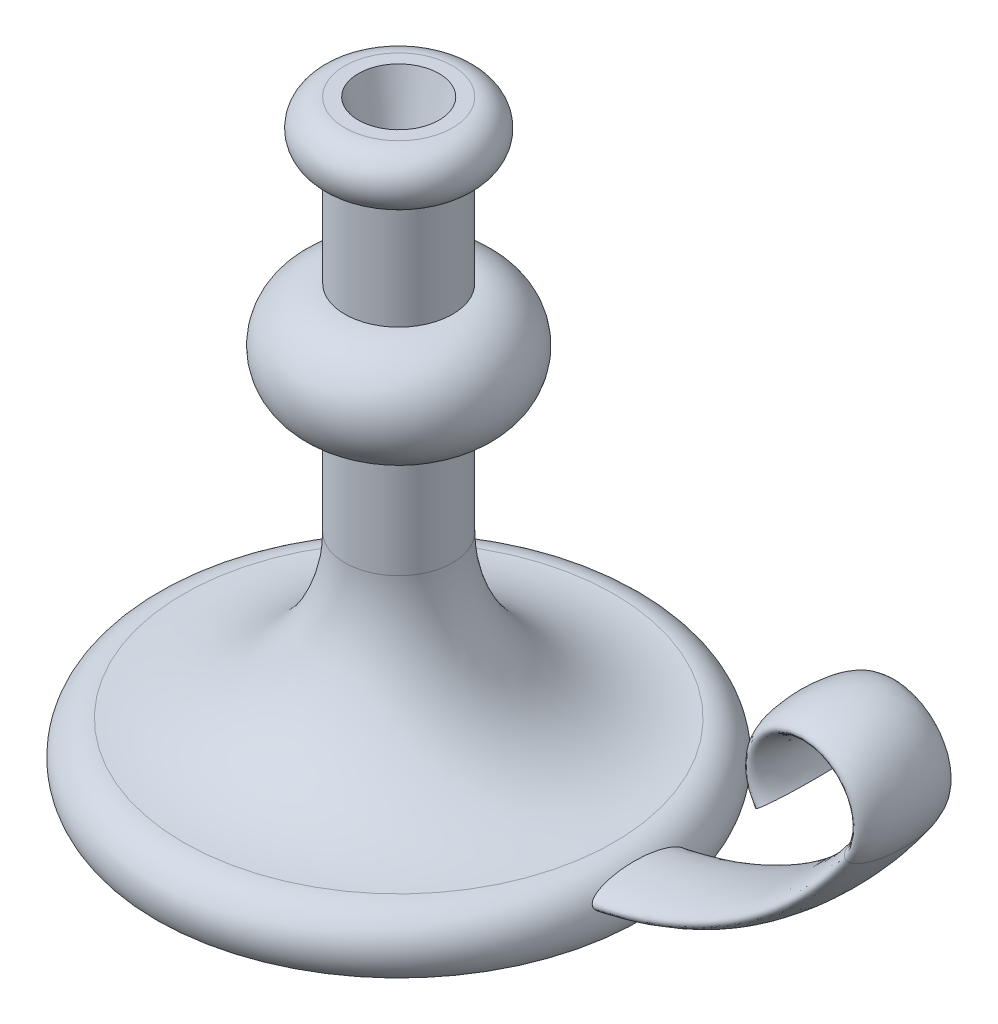
SolidWorks part; units mm, degrees
ref_plane "Front Plane" through (0, 0, 0) normal (0, 0, 1) x (1, 0, 0)
ref_plane "Top Plane" through (0, 0, 0) normal (0, 1, 0) x (1, 0, 0)
ref_plane "Right Plane" through (0, 0, 0) normal (1, 0, 0) x (0, 0, -1)
sketch "Sketch1" plane through (0, 0, 0) normal (0, 0, 1) x (1, 0, 0)
  line L0 (0, 0) -> (0, 220)
  line L1 (0, 220) -> (20, 220)
  line L2 (0, 0) -> (90, 0)
  line L3 (20, 200) -> (20, 160)
  line L4 (20, 120) -> (20, 80)
  arc A0 (20, 220) -> (20, 200) centre (20, 210) cw
  arc A1 (20, 160) -> (20, 120) centre (20, 140) cw
  arc A2 (20, 80) -> (80, 20) centre (80, 80) ccw
  arc A3 (80, 20) -> (90, 0) centre (80, 7.5) cw
  dimension "D7" = 60
  dimension "D6" = 20
  dimension "D8" = 12.5
  dimension "D4" = 10
  dimension "D9" = 80
  dimension "D1" = 20
  dimension "D2" = 220
  dimension "D3" = 90
  dimension "D5" = 40
revolve "Revolve1" add sketch "Sketch1" angle 360 about L0
sketch "Sketch2" plane through (0, 0, 0) normal (0, 0, 1) x (1, 0, 0)
  line L0 (0, 10) -> (60, 10)
  line L3 (0, 164) -> (0, 92) construction
  line L4 (80, 20) -> (-80, 20) construction
  arc A0 (60, 10) -> (183.5921, 75) centre (60, 160) ccw
  arc A1 (183.5921, 75) -> (150.6342, 75) centre (167.1131, 86.3333) ccw
  dimension "D3" = 150
  dimension "D4" = 20
  dimension "D1" = 60
  dimension "D2" = 65
  dimension "D5" = 10
sketch "Sketch4" plane through (0, 0, 0) normal (1, 0, 0) x (0, 0, -1)
  line L0 (0, 164) -> (0, 92) construction
  ellipse E0 centre (0, 10) end of major axis (17.5, 10) minor radius 5
  dimension "D1" = 35
  dimension "D2" = 10
sweep "Sweep1" add profiles "Sketch4" path "Sketch2"
sketch "Sketch5" plane through (0, 220, 0) normal (0, 1, 0) x (1, 0, 0)
  circle A0 centre (0, 0) radius 15
  dimension "D1" = 30
extrude "Cut-Extrude1" cut sketch "Sketch5" against normal blind 25 draft 15
